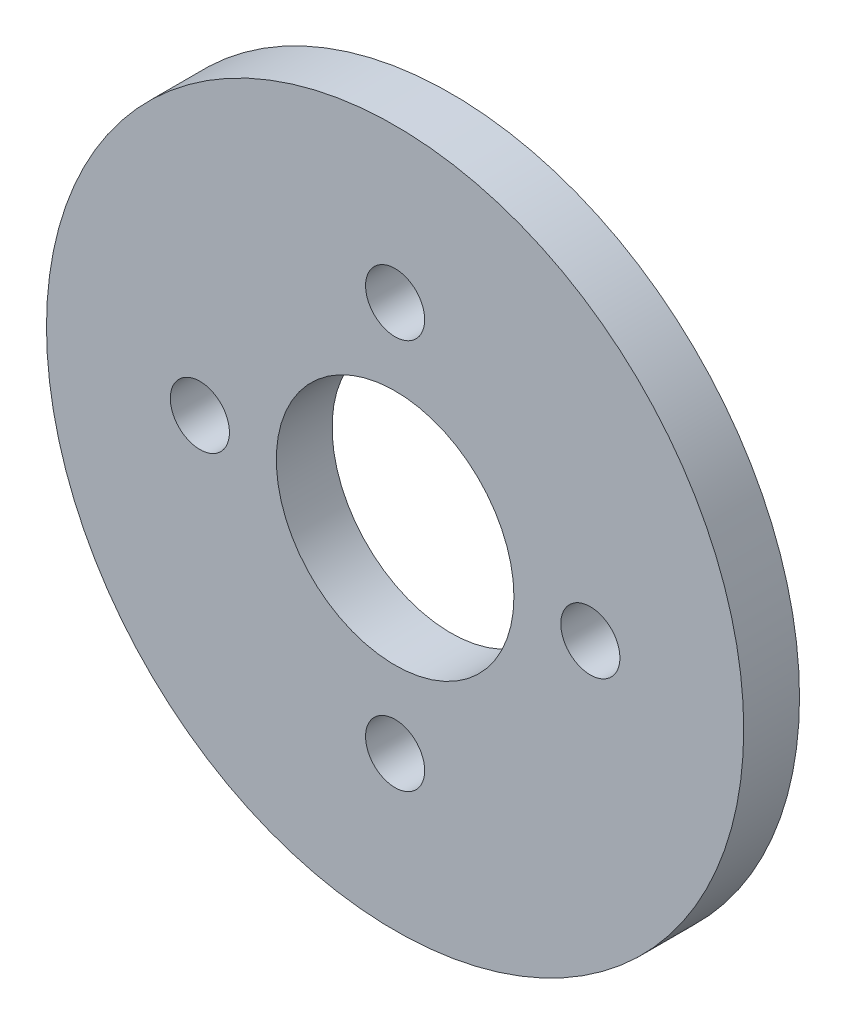
SolidWorks part; units mm, degrees
material "PETG"
ref_plane "Płaszczyzna przednia" through (0, 0, 0) normal (0, 0, 1) x (1, 0, 0)
ref_plane "Płaszczyzna górna" through (0, 0, 0) normal (0, 1, 0) x (1, 0, 0)
ref_plane "Płaszczyzna prawa" through (0, 0, 0) normal (1, 0, 0) x (0, 0, -1)
sketch "Szkic1" plane through (0, 0, 0) normal (0, 0, 1) x (1, 0, 0)
  circle A0 centre (0, 0) radius 62.5
  circle A1 centre (0, 0) radius 35 construction
  circle A2 centre (0, 35) radius 5.3
  circle A3 centre (35, 0) radius 5.3
  circle A4 centre (0, -35) radius 5.3
  circle A5 centre (-35, 0) radius 5.3
  circle A6 centre (0, 0) radius 21.3
  dimension "D1" = 125
  dimension "D2" = 70
  dimension "D3" = 10.6
  dimension "D6" = 42.6
extrude "Dodanie-wyciągnięcie3" add sketch "Szkic1" along normal blind 10 contours A0 A5 A1 A2 A3 A4 | A5 A1 A4 A3 A2 A6
